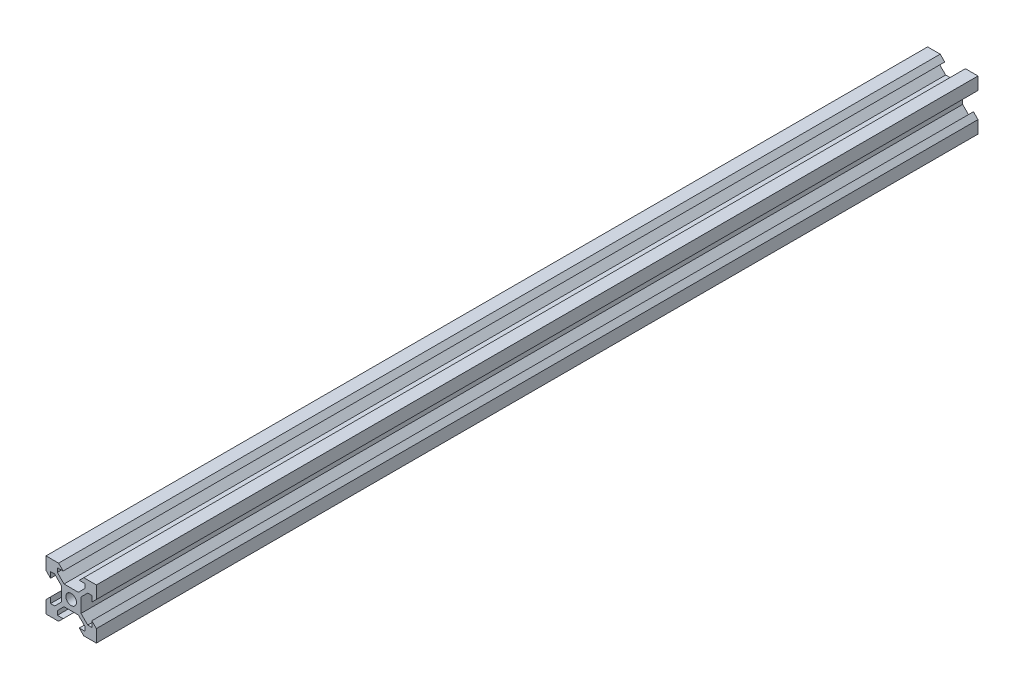
SolidWorks part; units mm, degrees
ref_plane "Front Plane" through (0, 0, 0) normal (0, 0, 1) x (1, 0, 0)
ref_plane "Top Plane" through (0, 0, 0) normal (0, 1, 0) x (1, 0, 0)
ref_plane "Right Plane" through (0, 0, 0) normal (1, 0, 0) x (0, 0, -1)
sketch "Sketch1" plane through (0, 0, 0) normal (0, 0, 1) x (1, 0, 0)
  line L0 (-10, 10) -> (-10, 5)
  line L1 (-10, 5) -> (-8.2, 3.2)
  line L2 (-8.2, 3.2) -> (-8.2, 5.4993)
  line L3 (-8.2, 5.4993) -> (-6.56, 5.4993)
  line L4 (-6.56, 5.4993) -> (-3.9007, 2.84)
  line L5 (-3.9007, 2.84) -> (-3.9007, -2.84)
  line L6 (-3.9007, -2.84) -> (-6.56, -5.4993)
  line L7 (-6.56, -5.4993) -> (-8.2, -5.4993)
  line L8 (-8.2, -5.4993) -> (-8.2, -3.2)
  line L9 (-8.2, -3.2) -> (-10, -5)
  line L10 (-10, -5) -> (-10, -10)
  line L11 (-10, -10) -> (-5, -10)
  line L12 (-5, -10) -> (-3.2, -8.2)
  line L13 (-3.2, -8.2) -> (-5.4993, -8.2)
  line L14 (-5.4993, -8.2) -> (-5.4993, -6.56)
  line L15 (-5.4993, -6.56) -> (-2.84, -3.9007)
  line L16 (-2.84, -3.9007) -> (2.84, -3.9007)
  line L17 (2.84, -3.9007) -> (5.4993, -6.56)
  line L18 (5.4993, -6.56) -> (5.4993, -8.2)
  line L19 (5.4993, -8.2) -> (3.2, -8.2)
  line L20 (3.2, -8.2) -> (5, -10)
  line L21 (5, -10) -> (10, -10)
  line L22 (10, -10) -> (10, -5)
  line L23 (10, -5) -> (8.2, -3.2)
  line L24 (8.2, -3.2) -> (8.2, -5.4993)
  line L25 (8.2, -5.4993) -> (6.56, -5.4993)
  line L26 (6.56, -5.4993) -> (3.9007, -2.84)
  line L27 (3.9007, -2.84) -> (3.9007, 2.84)
  line L28 (3.9007, 2.84) -> (6.56, 5.4993)
  line L29 (6.56, 5.4993) -> (8.2, 5.4993)
  line L30 (8.2, 5.4993) -> (8.2, 3.2)
  line L31 (8.2, 3.2) -> (10, 5)
  line L32 (10, 5) -> (10, 10)
  line L33 (10, 10) -> (5, 10)
  line L34 (5, 10) -> (3.2, 8.2)
  line L35 (3.2, 8.2) -> (5.4993, 8.2)
  line L36 (5.4993, 8.2) -> (5.4993, 6.56)
  line L37 (5.4993, 6.56) -> (2.84, 3.9007)
  line L38 (2.84, 3.9007) -> (-2.84, 3.9007)
  line L39 (-2.84, 3.9007) -> (-5.4993, 6.56)
  line L40 (-5.4993, 6.56) -> (-5.4993, 8.2)
  line L41 (-5.4993, 8.2) -> (-3.2, 8.2)
  line L42 (-3.2, 8.2) -> (-5, 10)
  line L43 (-5, 10) -> (-10, 10)
  circle A0 centre (0, 0) radius 2.1
extrude "Boss-Extrude1" add sketch "Sketch1" against normal blind 350
